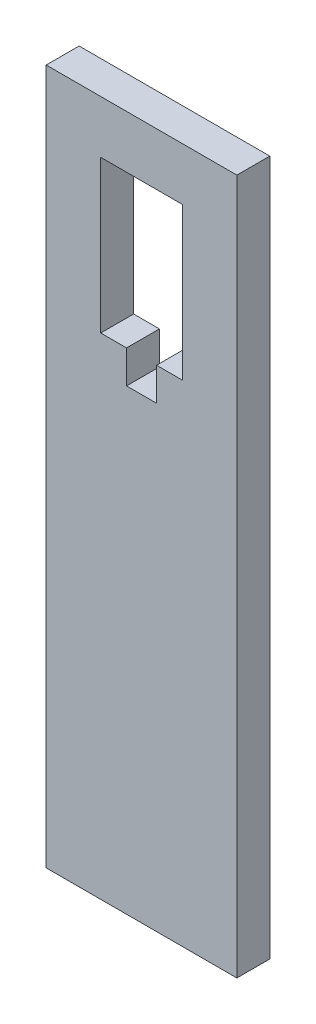
SolidWorks part; units mm, degrees
ref_plane "Front Plane" through (0, 0, 0) normal (0, 0, 1) x (1, 0, 0)
ref_plane "Top Plane" through (0, 0, 0) normal (0, 1, 0) x (1, 0, 0)
ref_plane "Right Plane" through (0, 0, 0) normal (1, 0, 0) x (0, 0, -1)
sketch "Sketch1" plane through (0, 0, 0) normal (0, 0, 1) x (1, 0, 0)
  line L1 (-18.5582, 31.0897) -> (10.4018, 31.0897)
  line L2 (-18.5582, 31.0897) -> (-18.5582, -43.4103)
  line L3 (-18.5582, -43.4103) -> (10.4018, -43.4103)
  line L4 (10.4018, 31.0897) -> (10.4018, -43.4103)
  dimension "D1" = 28.96
  dimension "D2" = 74.5
extrude "Boss-Extrude1" add sketch "Sketch1" along normal blind 5
sketch "Sketch2" plane through (0, 31.0897, 0) normal (0, 1, 0) x (1, 0, 0)
  line L0 (-18.5582, 0) -> (-10.2782, 0)
  line L1 (10.4018, 0) -> (-18.5582, 0) construction
  line L2 (-10.2782, 0) -> (-10.2782, -5)
  line L3 (10.4018, -5) -> (-18.5582, -5) construction
  line L4 (-10.2782, -5) -> (-18.5582, -5)
  line L5 (-18.5582, -5) -> (-18.5582, 0)
  line L6 (10.4018, 0) -> (2.1218, 0)
  line L7 (2.1218, 0) -> (2.1218, -5)
  line L8 (2.1218, -5) -> (10.4018, -5)
  line L9 (10.4018, -5) -> (10.4018, 0)
  dimension "D1" = 12.4
extrude "Boss-Extrude2" add sketch "Sketch2" along normal blind 23.11
sketch "Sketch3" plane through (0, 54.1997, 0) normal (0, 1, 0) x (1, 0, 0)
  line L1 (-18.5582, 0) -> (10.4018, 0)
  line L2 (-18.5582, 0) -> (-18.5582, -5)
  line L3 (-18.5582, -5) -> (10.4018, -5)
  line L4 (10.4018, 0) -> (10.4018, -5)
extrude "Boss-Extrude3" add sketch "Sketch3" along normal blind 8
sketch "Sketch4" plane through (0, 31.0897, 0) normal (0, 1, 0) x (1, 0, 0)
  line L0 (10.4018, 0) -> (-18.5582, 0) construction
  line L1 (-6.3582, 0) -> (-1.7982, 0)
  line L2 (-6.3582, 0) -> (-6.3582, -5)
  line L3 (-6.3582, -5) -> (-1.7982, -5)
  line L4 (-1.7982, 0) -> (-1.7982, -5)
  line L5 (-18.5582, -5) -> (10.4018, -5) construction
  line L6 (-18.5582, 0) -> (-18.5582, -5) construction
  line L7 (10.4018, -5) -> (10.4018, 0) construction
  dimension "D1" = 12.2
  dimension "D2" = 12.2
extrude "Cut-Extrude1" cut sketch "Sketch4" against normal blind 5
